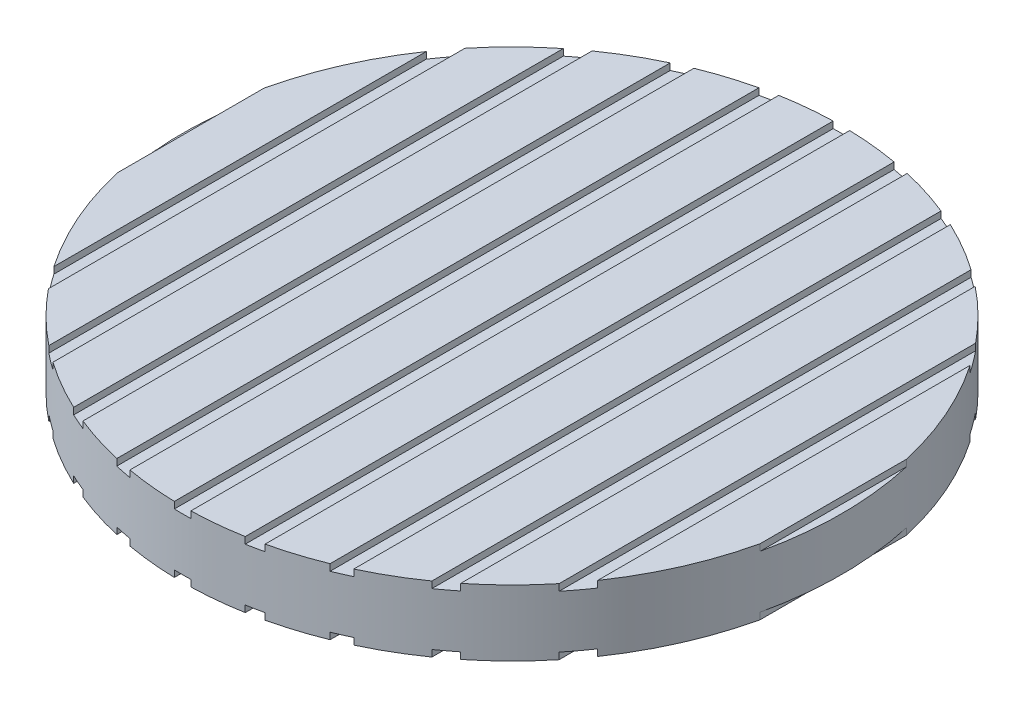
SolidWorks part; units mm, degrees
ref_plane "Front Plane" through (0, 0, 0) normal (0, 0, 1) x (1, 0, 0)
ref_plane "Top Plane" through (0, 0, 0) normal (0, 1, 0) x (1, 0, 0)
ref_plane "Right Plane" through (0, 0, 0) normal (1, 0, 0) x (0, 0, -1)
sketch "Sketch1" plane through (0, 0, 0) normal (0, 1, 0) x (1, 0, 0)
  circle A0 centre (-5.3482, -2.1046) radius 5
  dimension "D1" = 10
extrude "Boss-Extrude1" add sketch "Sketch1" along normal blind 1
sketch "Sketch2" plane through (0, 1, 0) normal (0, 1, 0) x (1, 0, 0)
  line L0 (-10.4732, 2.8954) -> (-10.4732, -7.1046)
  line L1 (-11.4732, 2.8954) -> (-11.2232, 2.8954)
  line L2 (-11.4732, 2.8954) -> (-11.4732, -7.1046)
  line L3 (-11.4732, -7.1046) -> (-11.2232, -7.1046)
  line L4 (-11.2232, 2.8954) -> (-11.2232, -7.1046)
  line L5 (-10.4732, 2.8954) -> (-10.2232, 2.8954)
  line L6 (-10.2232, 2.8954) -> (-10.2232, -7.1046)
  line L7 (-10.4732, -7.1046) -> (-10.2232, -7.1046)
  line L8 (-9.4732, 2.8954) -> (-9.4732, -7.1046)
  line L9 (-9.4732, 2.8954) -> (-9.2232, 2.8954)
  line L10 (-9.2232, 2.8954) -> (-9.2232, -7.1046)
  line L11 (-9.4732, -7.1046) -> (-9.2232, -7.1046)
  line L12 (-8.4732, 2.8954) -> (-8.4732, -7.1046)
  line L13 (-8.4732, 2.8954) -> (-8.2232, 2.8954)
  line L14 (-8.2232, 2.8954) -> (-8.2232, -7.1046)
  line L15 (-8.4732, -7.1046) -> (-8.2232, -7.1046)
  line L16 (-7.4732, 2.8954) -> (-7.4732, -7.1046)
  line L17 (-7.4732, 2.8954) -> (-7.2232, 2.8954)
  line L18 (-7.2232, 2.8954) -> (-7.2232, -7.1046)
  line L19 (-7.4732, -7.1046) -> (-7.2232, -7.1046)
  line L20 (-6.4732, 2.8954) -> (-6.4732, -7.1046)
  line L21 (-6.4732, 2.8954) -> (-6.2232, 2.8954)
  line L22 (-6.2232, 2.8954) -> (-6.2232, -7.1046)
  line L23 (-6.4732, -7.1046) -> (-6.2232, -7.1046)
  line L24 (-5.4732, 2.8954) -> (-5.4732, -7.1046)
  line L25 (-5.4732, 2.8954) -> (-5.2232, 2.8954)
  line L26 (-5.2232, 2.8954) -> (-5.2232, -7.1046)
  line L27 (-5.4732, -7.1046) -> (-5.2232, -7.1046)
  line L28 (-4.4732, 2.8954) -> (-4.4732, -7.1046)
  line L29 (-4.4732, 2.8954) -> (-4.2232, 2.8954)
  line L30 (-4.2232, 2.8954) -> (-4.2232, -7.1046)
  line L31 (-4.4732, -7.1046) -> (-4.2232, -7.1046)
  line L32 (-3.4732, 2.8954) -> (-3.4732, -7.1046)
  line L33 (-3.4732, 2.8954) -> (-3.2232, 2.8954)
  line L34 (-3.2232, 2.8954) -> (-3.2232, -7.1046)
  line L35 (-3.4732, -7.1046) -> (-3.2232, -7.1046)
  line L36 (-2.4732, 2.8954) -> (-2.4732, -7.1046)
  line L37 (-2.4732, 2.8954) -> (-2.2232, 2.8954)
  line L38 (-2.2232, 2.8954) -> (-2.2232, -7.1046)
  line L39 (-2.4732, -7.1046) -> (-2.2232, -7.1046)
  line L40 (-1.4732, 2.8954) -> (-1.4732, -7.1046)
  line L41 (-1.4732, 2.8954) -> (-1.2232, 2.8954)
  line L42 (-1.2232, 2.8954) -> (-1.2232, -7.1046)
  line L43 (-1.4732, -7.1046) -> (-1.2232, -7.1046)
  line L44 (-0.4732, 2.8954) -> (-0.4732, -7.1046)
  line L45 (-0.4732, 2.8954) -> (-0.2232, 2.8954)
  line L46 (-0.2232, 2.8954) -> (-0.2232, -7.1046)
  line L47 (-0.4732, -7.1046) -> (-0.2232, -7.1046)
  line L48 (0.5268, 2.8954) -> (0.5268, -7.1046)
  line L49 (0.5268, 2.8954) -> (0.7768, 2.8954)
  line L50 (0.7768, 2.8954) -> (0.7768, -7.1046)
  line L51 (0.5268, -7.1046) -> (0.7768, -7.1046)
  line L52 (1.5268, 2.8954) -> (1.5268, -7.1046)
  line L53 (1.5268, 2.8954) -> (1.7768, 2.8954)
  line L54 (1.7768, 2.8954) -> (1.7768, -7.1046)
  line L55 (1.5268, -7.1046) -> (1.7768, -7.1046)
  line L56 (2.5268, 2.8954) -> (2.5268, -7.1046)
  line L57 (2.5268, 2.8954) -> (2.7768, 2.8954)
  line L58 (2.7768, 2.8954) -> (2.7768, -7.1046)
  line L59 (2.5268, -7.1046) -> (2.7768, -7.1046)
  line L60 (-11.4732, 2.8954) -> (-10.4732, 2.8954) construction
  circle A0 centre (-5.3482, -2.1046) radius 5 construction
  point P6 (-5.3482, 2.8954)
  dimension "D1" = 0.25
  dimension "D3" = 1
  dimension "D2" = 15
extrude "Cut-Extrude1" cut sketch "Sketch2" against normal blind 0.1
ref_plane "Plane1" through (0, 0.5, 0) normal (0, -1, 0) x (-1, 0, 0)
mirror "Mirror1" about plane through (0, 0.5, 0) normal (0, -1, 0) of "Cut-Extrude1"
